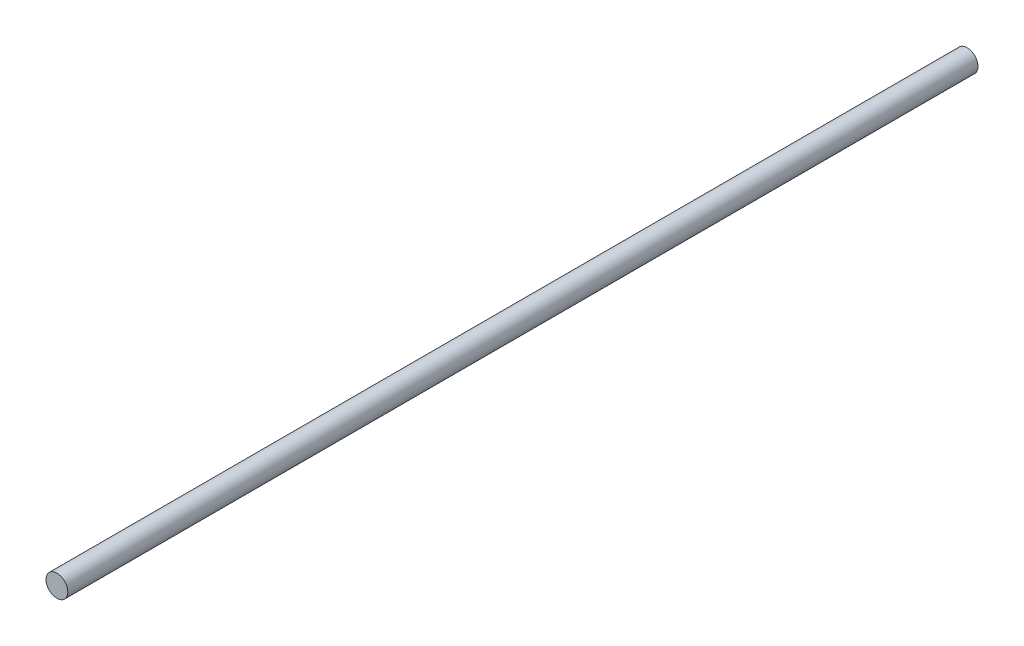
SolidWorks part; units mm, degrees
material "AISI 4130 Steel, annealed at 865C"
ref_plane "Front Plane" through (0, 0, 0) normal (0, 0, 1) x (1, 0, 0)
ref_plane "Top Plane" through (0, 0, 0) normal (0, 1, 0) x (1, 0, 0)
ref_plane "Right Plane" through (0, 0, 0) normal (1, 0, 0) x (0, 0, -1)
sketch "Sketch1" plane through (0, 0, 0) normal (0, 0, 1) x (1, 0, 0)
  circle A0 centre (0, 0) radius 12.7
  dimension "D1" = 25.4
extrude "Boss-Extrude1" add sketch "Sketch1" along normal blind 1060
